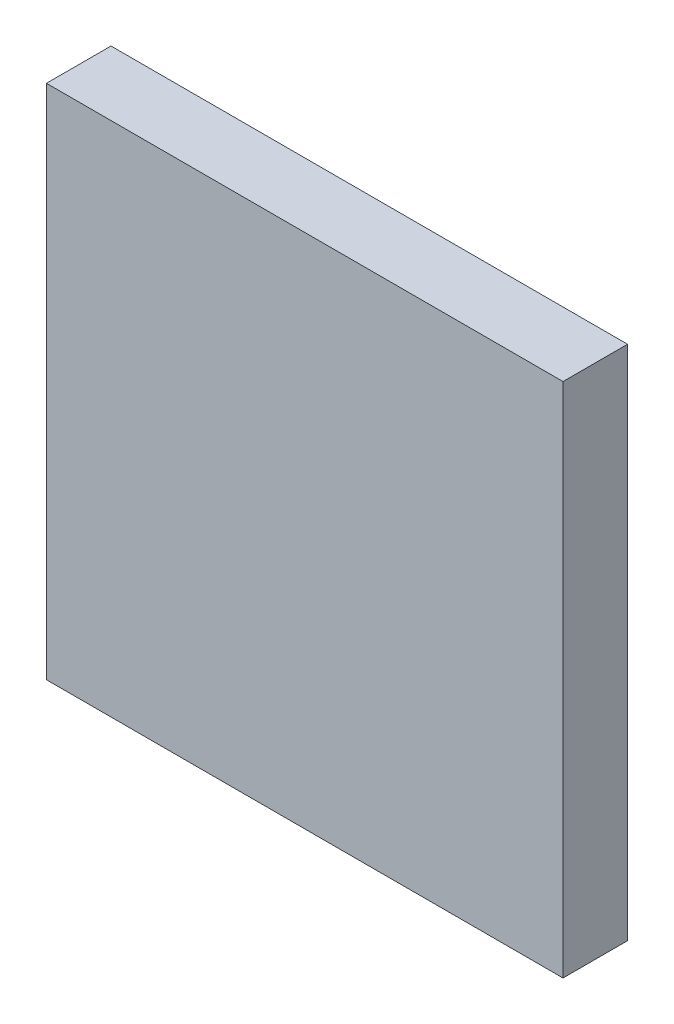
SolidWorks part; units mm, degrees
material "Glass"
ref_plane "Front Plane" through (0, 0, 0) normal (0, 0, 1) x (1, 0, 0)
ref_plane "Top Plane" through (0, 0, 0) normal (0, 1, 0) x (1, 0, 0)
ref_plane "Right Plane" through (0, 0, 0) normal (1, 0, 0) x (0, 0, -1)
sketch "Sketch1" plane through (0, 0, 0) normal (0, 0, 1) x (1, 0, 0)
  line L1 (-200, 200) -> (200, 200)
  line L2 (-200, 200) -> (-200, -200)
  line L3 (-200, -200) -> (200, -200)
  line L4 (200, 200) -> (200, -200)
  line L5 (-200, 200) -> (200, -200) construction
  line L6 (-200, -200) -> (200, 200) construction
  point P0 (0, 0)
  dimension "D1" = 400
  dimension "D2" = 400
extrude "Boss-Extrude1" add sketch "Sketch1" along normal blind 50
